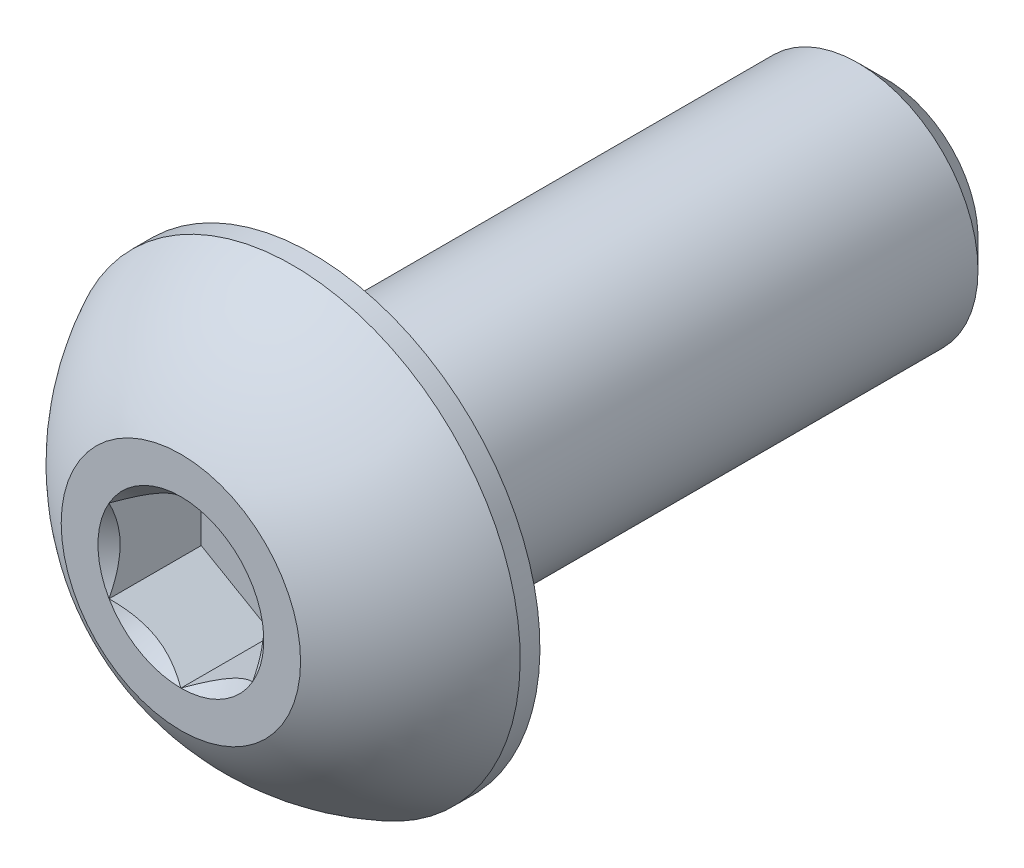
SolidWorks part; units mm, degrees
ref_plane "Front" through (0, 0, 0) normal (0, 0, 1) x (1, 0, 0)
ref_plane "Top" through (0, 0, 0) normal (0, 1, 0) x (1, 0, 0)
ref_plane "Right" through (0, 0, 0) normal (1, 0, 0) x (0, 0, -1)
sketch "Sketch1" plane through (0, 0, 0) normal (1, 0, 0) x (0, 0, -1)
  line L2 (-6, 2.5) -> (6, 2.5)
  line L3 (6, 2.5) -> (6, 0)
  line L4 (6, 0) -> (-6, 0)
  line L6 (-6.4125, 4.75) -> (-6, 4.75) construction
  line L7 (6, 2.5) -> (6, -2.5) construction
  line L8 (-8.75, 0) -> (-6, 0) construction
  line L9 (-6, 4.75) -> (-6, -4.75) construction
  line L11 (-6, 2.5) -> (-6, 0)
  line L13 (-8.75, 1.5) -> (-8.75, -1.5) construction
  line L14 (-8.75, 1.5) -> (-8.75, 2.5) construction
  line L15 (5.95, 2.5866) -> (6.35, 1.8938) construction
  line L16 (6.35, 1.8938) -> (6.75, 2.5866) construction
  line L17 (6.75, 2.5866) -> (5.95, 2.5866) construction
  line L18 (6, 2.5) -> (6.7, 2.5) construction
  line L19 (6.35, 2.5866) -> (6.35, 2.5) construction
  line L20 (6.35, 2.5) -> (6.35, 1.9804) construction
  line L21 (6.35, 1.9804) -> (6.35, 1.8938) construction
  line L22 (6.3, 1.9804) -> (6.4, 1.9804)
  line L23 (5.975, 2.5433) -> (6.725, 2.5433)
  line L24 (6.4, 1.9804) -> (6.725, 2.5433)
  line L25 (6.3, 1.9804) -> (5.975, 2.5433)
  line L26 (5.4, 2.5) -> (6, 1.9)
  arc A3 (-8.75, 2.5) -> (-6.4125, 4.75) centre (-4.0919, 0) cw construction
  point P29 (6.35, 2.5433)
  point P30 (4, -2.5)
  point P33 (0, 0)
  dimension "Thread Size" = 5
  dimension "D1" = 0.4125
  dimension "Head Height" = 2.75
  dimension "Head Diameter" = 9.5
  dimension "Length" = 12
  dimension "Drive Size" = 3
  dimension "Thread Pitch" = 0.8
  dimension "D3" = 0.1
  dimension "D2" = 0.6
  dimension "D4" = 45
  dimension "D5" = 2
sketch "Sketch10" plane through (0, 0, 0) normal (1, 0, 0) x (0, 0, -1)
  line L0 (5.4, 2.5) -> (6, 1.9) construction
  line L1 (5.4, 2.5) -> (6, 1.9)
  line L4 (6, 2.5) -> (-6, 2.5)
  line L5 (6, 0) -> (6, 2.5)
  line L6 (-6, 0) -> (6, 0)
  line L7 (-6, 2.5) -> (-6, 0)
  line L8 (5.4, 2.5) -> (-6, 2.5)
  line L9 (6, 0) -> (6, 1.9)
  line L10 (-6, 0) -> (6, 0)
  line L11 (-6, 2.5) -> (-6, 0)
  dimension "D1" = 0
revolve "Revolve3" add sketch "Sketch10" angle 360 about L8
sketch "Sketch7" plane through (0, 0, 0) normal (1, 0, 0) x (0, 0, -1)
  line L6 (-6.4125, 4.75) -> (-6, 4.75) construction
  line L8 (-8.75, 0) -> (-6, 0) construction
  line L11 (-6, 4.75) -> (-6, -4.75) construction
  line L12 (-6.4125, 4.75) -> (-6, 4.75)
  line L13 (-8.75, 0) -> (-6, 0)
  line L14 (-8.75, 1.5) -> (-8.75, -1.5) construction
  line L15 (-6, 4.75) -> (-6, 0)
  line L16 (-8.75, 2.5) -> (-8.75, 0)
  arc A2 (-6.4125, 4.75) -> (-8.75, 2.5) centre (-4.0919, 0) ccw construction
  arc A3 (-6.4125, 4.75) -> (-8.75, 2.5) centre (-4.0919, 0) ccw
revolve "Revolve2" add sketch "Sketch7" angle 360 mid plane about L13
sketch "Sketch5" plane through (0, 0, 8.75) normal (0, 0, 1) x (1, 0, 0)
  line L1 (1.5, -0.866) -> (1.5, 0.866)
  line L2 (1.5, 0.866) -> (0, 1.7321)
  line L3 (0, 1.7321) -> (-1.5, 0.866)
  line L4 (-1.5, 0.866) -> (-1.5, -0.866)
  line L5 (-1.5, -0.866) -> (0, -1.7321)
  line L6 (0, -1.7321) -> (1.5, -0.866)
  circle A0 centre (0, 0) radius 1.5 construction
extrude "Cut-Extrude2" cut sketch "Sketch5" against normal blind 1.925
sketch "Sketch6" plane through (0, 0, 8.75) normal (0, 0, 1) x (1, 0, 0)
  circle A0 centre (0, 0) radius 1.7321
extrude "Cut-Extrude3" cut sketch "Sketch6" against normal blind 1.925 draft 45
sketch "Sketch9" plane through (0, 0, 6) normal (0, 0, -1) x (-1, 0, 0)
  circle A0 centre (0, 0) radius 2.5 construction
  circle A4 centre (0, 0) radius 2.5
sketch "Sketch11" plane through (0, 0, -6) normal (0, 0, -1) x (-1, 0, 0)
  circle A0 centre (0, 0) radius 2.5 construction
  circle A1 centre (0, 0) radius 2.5
sketch "Sketch12" plane through (0, 0, 0) normal (1, 0, 0) x (0, 0, -1)
  line L0 (6.3, 1.9804) -> (6.4, 1.9804) construction
  line L1 (6.4, 1.9804) -> (6.725, 2.5433) construction
  line L2 (5.975, 2.5433) -> (6.725, 2.5433) construction
  line L3 (6.3, 1.9804) -> (5.975, 2.5433) construction
  line L4 (6.3, 1.9804) -> (6.4, 1.9804)
  line L5 (6.4, 1.9804) -> (6.725, 2.5433)
  line L6 (5.975, 2.5433) -> (6.725, 2.5433)
  line L7 (6.3, 1.9804) -> (5.975, 2.5433)
equation "\"D1@Cut-Extrude2\" = \"Head Height@Sketch1\" * .7"
equation "\"D1@Sketch1\" = \"Head Height@Sketch1\" * .15"
equation "\"D1@Cut-Extrude3\" = \"D1@Cut-Extrude2\""
equation "\"D3@Sketch1\" = \"Thread Pitch@Sketch1\" / 8"
equation "\"D2@Sketch1\" = \"Thread Pitch@Sketch1\" * 0.75"
equation "\"D5@Sketch1\" = \"Thread Pitch@Sketch1\" * 2.5"
